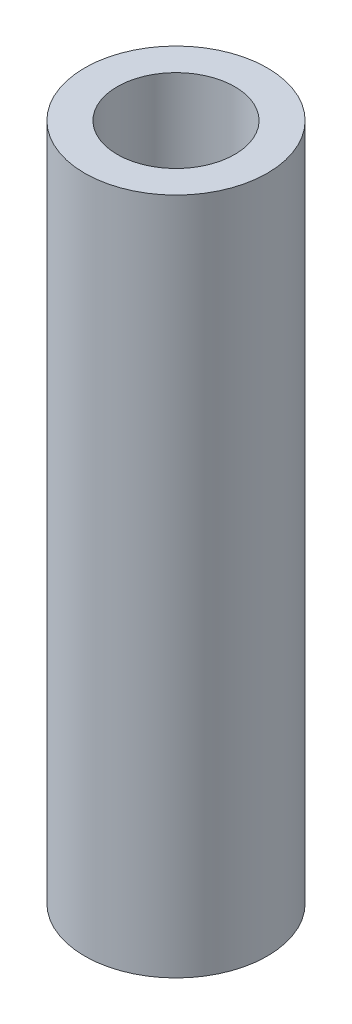
SolidWorks part; units mm, degrees
ref_plane "Front Plane" through (0, 0, 0) normal (0, 0, 1) x (1, 0, 0)
ref_plane "Top Plane" through (0, 0, 0) normal (0, 1, 0) x (1, 0, 0)
ref_plane "Right Plane" through (0, 0, 0) normal (1, 0, 0) x (0, 0, -1)
sketch "Sketch1" plane through (0, 0, 0) normal (0, 1, 0) x (1, 0, 0)
  circle A0 centre (0, 0) radius 10.1
  circle A1 centre (0, 0) radius 6.5
  dimension "D1" = 20.2
  dimension "D2" = 13
extrude "Boss-Extrude1" add sketch "Sketch1" along normal blind 75
